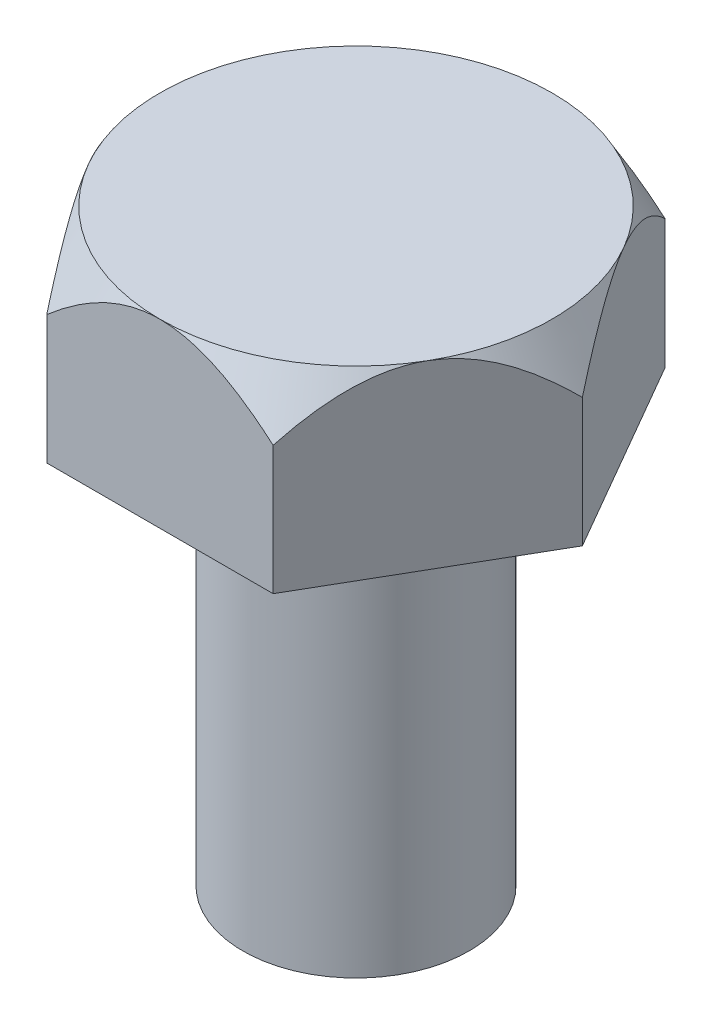
SolidWorks part; units mm, degrees
ref_plane "Front Plane" through (0, 0, 0) normal (0, 0, 1) x (1, 0, 0)
ref_plane "Top Plane" through (0, 0, 0) normal (0, 1, 0) x (1, 0, 0)
ref_plane "Right Plane" through (0, 0, 0) normal (1, 0, 0) x (0, 0, -1)
sketch "Sketch1" plane through (0, 0, 0) normal (0, 1, 0) x (1, 0, 0)
  line L1 (5, 0) -> (2.5, 4.3301)
  line L2 (2.5, 4.3301) -> (-2.5, 4.3301)
  line L3 (-2.5, 4.3301) -> (-5, 0)
  line L4 (-5, 0) -> (-2.5, -4.3301)
  line L5 (-2.5, -4.3301) -> (2.5, -4.3301)
  line L6 (2.5, -4.3301) -> (5, 0)
  circle A0 centre (0, 0) radius 4.3301 construction
  dimension "D1" = 10
extrude "Boss-Extrude1" add sketch "Sketch1" along normal mid plane 4
sketch "Sketch2" plane through (0, 2, 0) normal (0, 1, 0) x (1, 0, 0)
  circle A0 centre (0, 0) radius 4.3301
extrude "Cut-Extrude2" cut sketch "Sketch2" against normal through all draft 30 flip side to cut contours A0
sketch "Sketch3" plane through (0, -2, 0) normal (0, -1, 0) x (1, 0, 0)
  circle A0 centre (0, 0) radius 2.5
  dimension "D1" = 5
extrude "Boss-Extrude2" add sketch "Sketch3" along normal blind 9
